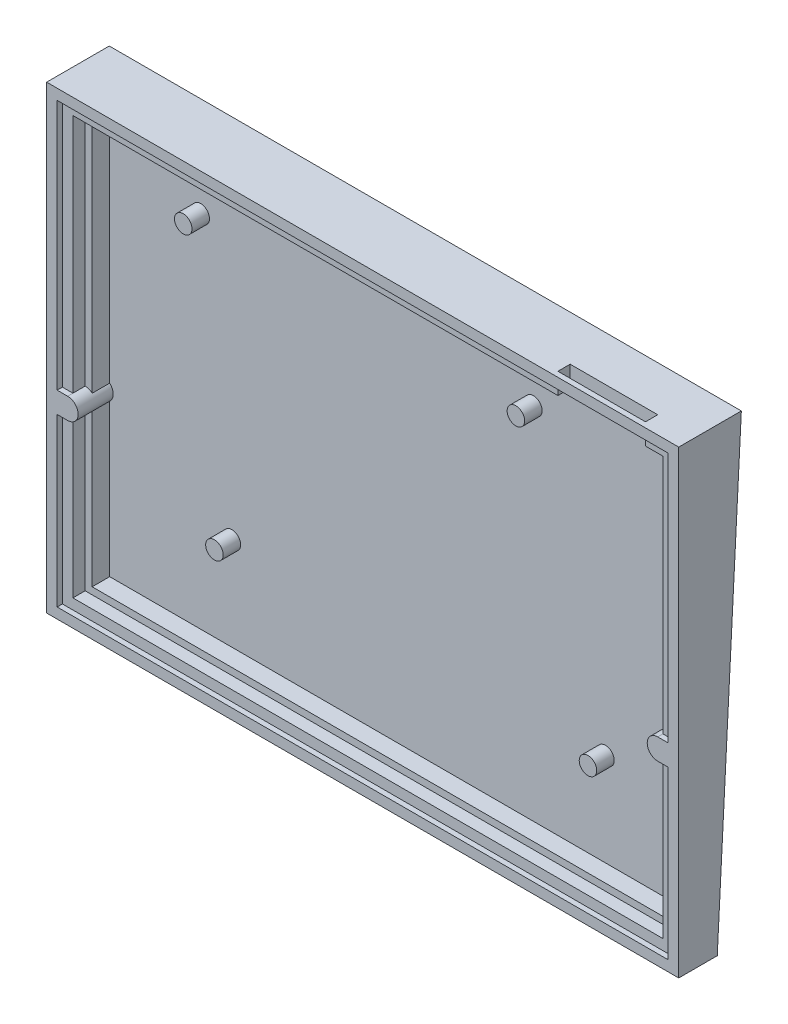
SolidWorks part; units mm, degrees
ref_plane "前视基准面" through (0, 0, 0) normal (0, 0, 1) x (1, 0, 0)
ref_plane "上视基准面" through (0, 0, 0) normal (0, 1, 0) x (1, 0, 0)
ref_plane "右视基准面" through (0, 0, 0) normal (1, 0, 0) x (0, 0, -1)
sketch "Model" plane through (0, 0, 0) normal (0, 0, 1) x (1, 0, 0)
  line L0 (565.3976, -76.1053) -> (390.8957, -76.1053)
  line L1 (390.8957, -76.1053) -> (390.8957, -28.4789)
  line L2 (390.8957, -22.4789) -> (390.8957, 49.195)
  line L3 (390.8957, 49.195) -> (565.3976, 49.195)
  line L4 (390.8957, -22.4789) -> (393.8957, -22.4789)
  line L5 (390.8957, -28.4789) -> (393.8957, -28.4789)
  line L6 (565.3976, -22.4796) -> (562.3976, -22.4796)
  line L7 (565.3976, -28.4796) -> (562.3976, -28.4796)
  line L8 (565.3976, 49.195) -> (565.3976, -22.4796)
  line L9 (565.3976, -28.4796) -> (565.3976, -76.1053)
  line L10 (562.3976, 46.195) -> (562.3976, -22.4796)
  line L11 (393.8957, -22.4789) -> (393.8957, 46.195)
  line L12 (393.8957, 46.195) -> (562.3976, 46.195)
  line L13 (393.8957, -73.1053) -> (393.8957, -28.4789)
  line L14 (562.3976, -73.1053) -> (393.8957, -73.1053)
  line L15 (562.3976, -28.4796) -> (562.3976, -73.1053)
  line L16 (387.8957, -79.1053) -> (387.8957, 52.195)
  line L17 (387.8957, 52.195) -> (568.3976, 52.195)
  line L18 (568.3976, 52.195) -> (568.3976, -79.1053)
  line L19 (568.3976, -79.1053) -> (387.8957, -79.1053)
  line L20 (560.3976, -71.1053) -> (395.8957, -71.1053)
  line L21 (395.8957, -71.1053) -> (395.8957, -27.715)
  line L22 (560.3976, -27.7157) -> (560.3976, -71.1053)
  line L23 (560.3976, 44.195) -> (560.3976, -23.2435)
  line L24 (395.8957, -23.2428) -> (395.8957, 44.195)
  line L25 (395.8957, 44.195) -> (560.3976, 44.195)
  line L26 (393.8957, -22.4789) -> (390.8957, -22.4789)
  line L27 (390.8957, 49.195) -> (565.3976, 49.195)
  line L28 (565.3976, -22.4796) -> (562.3976, -22.4796)
  line L29 (562.3976, 46.195) -> (393.8957, 46.195)
  arc A0 (393.8957, -28.4789) -> (393.8957, -22.4789) centre (393.8957, -25.4789) ccw
  arc A1 (562.3976, -22.4796) -> (562.3976, -28.4796) centre (562.3976, -25.4796) ccw
extrude "凸台-拉伸3" add sketch "Model" along normal blind 8.5 contours L7 L15 L14 L13 L5 L1 L0 L9 | L11 L12 L10 L6 L8 L3 L2 L4
sketch "草图4" plane through (0, 0, 0) normal (0, 0, -1) x (-1, 0, 0)
  line L0 (-568.3976, -79.1053) -> (-568.3976, 52.195)
  line L1 (-568.3976, 52.195) -> (-387.8957, 52.195)
  line L2 (-387.8957, 52.195) -> (-387.8957, -79.1053)
  line L3 (-387.8957, -79.1053) -> (-568.3976, -79.1053)
  line L4 (-390.8957, -76.1053) -> (-565.3976, -76.1053)
  line L5 (-565.3976, -76.1053) -> (-565.3976, -28.4796)
  line L6 (-565.3976, -28.4796) -> (-562.3976, -28.4796)
  line L7 (-562.3976, -22.4796) -> (-565.3976, -22.4796)
  line L8 (-565.3976, -22.4796) -> (-565.3976, 49.195)
  line L9 (-565.3976, 49.195) -> (-390.8957, 49.195)
  line L10 (-390.8957, 49.195) -> (-390.8957, -22.4789)
  line L11 (-390.8957, -22.4789) -> (-393.8957, -22.4789)
  line L12 (-393.8957, -28.4789) -> (-390.8957, -28.4789)
  line L13 (-390.8957, -28.4789) -> (-390.8957, -76.1053)
  line L14 (-393.8957, -73.1053) -> (-393.8957, -28.4789) construction
  arc A0 (-393.8957, -22.4789) -> (-393.8957, -28.4789) centre (-393.8957, -25.4789) ccw
  arc A1 (-562.3976, -28.4796) -> (-562.3976, -22.4796) centre (-562.3976, -25.4796) ccw
  arc A2 (-562.3976, -28.4796) -> (-562.3976, -22.4796) centre (-562.3976, -25.4796) ccw construction
  line M5 (-562.3976, -28.4796) -> (-565.3976, -28.4796)
  line M6 (-565.3976, -28.4796) -> (-565.3976, -76.1053)
  line M7 (-565.3976, -76.1053) -> (-390.8957, -76.1053)
  line M8 (-390.8957, -76.1053) -> (-390.8957, -28.4789)
  line M9 (-390.8957, -28.4789) -> (-393.8957, -28.4789)
extrude "凸台-拉伸5" add sketch "草图4" against normal blind 10 contours L3 L2 L1 L0 A1 L7 L8 L9 L10 L11 A0 M5 M9 M8 M7 M6
sketch "草图5" plane through (0, 0, 0) normal (0, 0, -1) x (-1, 0, 0)
  line L0 (-562.3976, -22.4796) -> (-562.3976, 46.195)
  line L1 (-562.3976, 46.195) -> (-393.8957, 46.195)
  line L2 (-393.8957, 46.195) -> (-393.8957, -22.4789)
  line L3 (-395.8957, -23.2428) -> (-395.8957, 44.195)
  line L4 (-395.8957, 44.195) -> (-560.3976, 44.195)
  line L5 (-560.3976, 44.195) -> (-560.3976, -23.2435)
  line L6 (-560.3976, -27.7157) -> (-560.3976, -71.1053)
  line L7 (-560.3976, -71.1053) -> (-395.8957, -71.1053)
  line L8 (-395.8957, -71.1053) -> (-395.8957, -27.715)
  line L9 (-393.8957, -28.4789) -> (-393.8957, -73.1053)
  line L10 (-393.8957, -73.1053) -> (-562.3976, -73.1053)
  line L11 (-562.3976, -73.1053) -> (-562.3976, -28.4796)
  arc A0 (-562.3976, -22.4796) -> (-560.3976, -23.2435) centre (-562.3976, -25.4796) cw
  arc A1 (-562.3976, -28.4796) -> (-560.3976, -27.7157) centre (-562.3976, -25.4796) ccw
  arc A2 (-393.8957, -28.4789) -> (-395.8957, -27.715) centre (-393.8957, -25.4789) cw
  arc A3 (-395.8957, -23.2428) -> (-393.8957, -22.4789) centre (-393.8957, -25.4789) cw
  arc A4 (-393.8957, -22.4789) -> (-393.8957, -28.4789) centre (-393.8957, -25.4789) ccw construction
  line M1 (-393.8957, 46.195) -> (-393.8957, -22.4789)
  arc M2 (-393.8957, -22.4789) -> (-393.8957, -28.4789) centre (-393.8957, -25.4789) ccw
  line M3 (-393.8957, -28.4789) -> (-393.8957, -73.1053)
  line M4 (-393.8957, -73.1053) -> (-562.3976, -73.1053)
  line M5 (-562.3976, -73.1053) -> (-562.3976, -28.4796)
  arc M6 (-562.3976, -28.4796) -> (-562.3976, -22.4796) centre (-562.3976, -25.4796) ccw
  line M7 (-562.3976, -22.4796) -> (-562.3976, 46.195)
  line M8 (-562.3976, 46.195) -> (-393.8957, 46.195)
extrude "凸台-拉伸6" add sketch "草图5" against normal blind 5 contours L5 L4 L3 M2 M1 M8 M7 M6 | L8 L7 L6 M6 M5 M4 M3 M2
sketch "草图8" plane through (0, 0, 5) normal (0, 0, 1) x (1, 0, 0)
  line L0 (393.8957, 46.195) -> (562.3976, 46.195) construction
  line L1 (557.3976, 46.195) -> (532.3976, 46.195)
  line L2 (557.3976, 46.195) -> (557.3976, 52.195)
  line L3 (557.3976, 52.195) -> (532.3976, 52.195)
  line L4 (532.3976, 46.195) -> (532.3976, 52.195)
  line L5 (568.3976, 52.195) -> (387.8957, 52.195) construction
  dimension "D1" = 5
  dimension "D2" = 25
extrude "切除-拉伸1" cut sketch "草图8" along normal blind 3.5
sketch "草图9" plane through (0, 0, 0) normal (0, 0, -1) x (-1, 0, 0)
  line L0 (-393.8957, 46.195) -> (-562.3976, 46.195) construction
  circle A0 centre (-430.8057, -44.5253) radius 2.5
  circle A1 centre (-537.4776, -44.5253) radius 2.5
  circle A2 centre (-421.8957, 31.665) radius 2.5
  circle A3 centre (-516.8957, 31.665) radius 2.5
  dimension "D1" = 36.91
  dimension "D2" = 28.58
  dimension "D3" = 24.92
  dimension "D4" = 28.58
  dimension "D5" = 95
  dimension "D6" = 28
  dimension "D7" = 14.53
  dimension "D8" = 14.53
extrude "凸台-拉伸7" add sketch "草图9" against normal blind 5 separate body
sketch "草图10" plane through (387.8957, 0, 0) normal (-1, 0, 0) x (0, 0, 1)
  line L2 (-1, -79.1053) -> (-7.8812, 52.195)
  line L4 (0, -79.1053) -> (0, 52.195)
  line L5 (0, 52.195) -> (-7.8812, 52.195)
  line L8 (0, -79.1053) -> (-1, -79.1053)
  point P0 (-4.5004, -80.6292)
  dimension "D1" = 11
  dimension "D2" = 3
extrude "凸台-拉伸8" add sketch "草图10" against normal up to surface (180.5019 mm away) up to face at (568.3976, -13.4551, 5)
